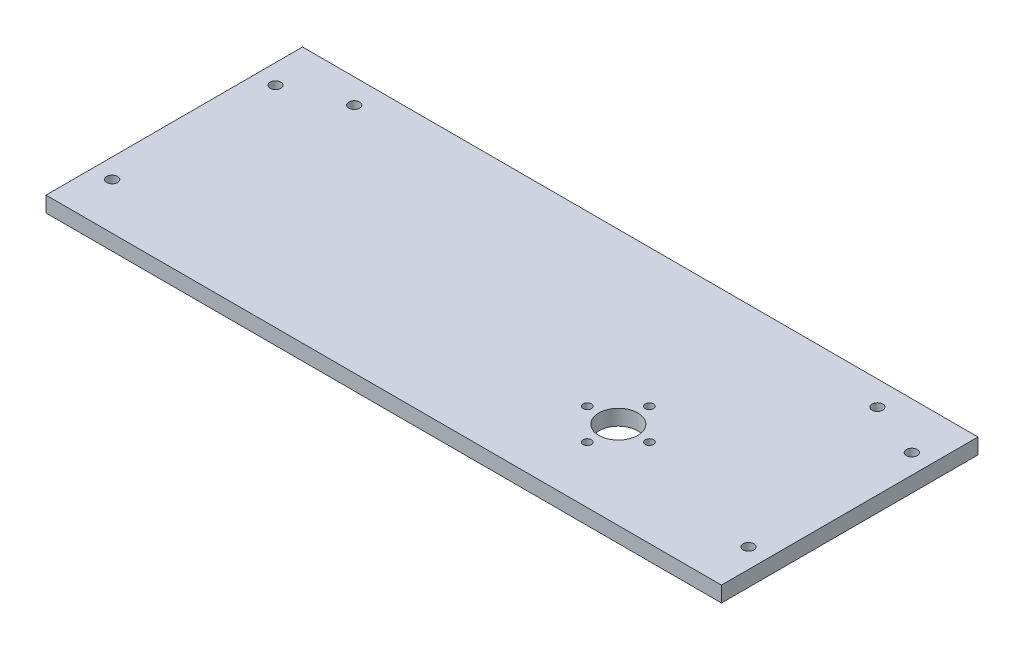
SolidWorks part; units mm, degrees
ref_plane "Front Plane" through (0, 0, 0) normal (0, 0, 1) x (1, 0, 0)
ref_plane "Top Plane" through (0, 0, 0) normal (0, 1, 0) x (1, 0, 0)
ref_plane "Right Plane" through (0, 0, 0) normal (1, 0, 0) x (0, 0, -1)
sketch "Sketch1" plane through (0, 0, 0) normal (0, 1, 0) x (1, 0, 0)
  line L1 (-138, 52.413) -> (138, 52.413)
  line L2 (-138, 52.413) -> (-138, -52.413)
  line L3 (-138, -52.413) -> (138, -52.413)
  line L4 (138, 52.413) -> (138, -52.413)
  line L5 (-138, 52.413) -> (138, -52.413) construction
  line L6 (-138, -52.413) -> (138, 52.413) construction
  point P0 (0, 0)
  dimension "D1" = 276
  dimension "D2" = 104.826
extrude "Boss-Extrude1" add sketch "Sketch1" along normal blind 6.35
sketch "Sketch2" plane through (0, 6.35, 0) normal (0, 1, 0) x (1, 0, 0)
  line L0 (138, 52.413) -> (-138, 52.413) construction
  line L1 (-138, -52.413) -> (138, -52.413) construction
  line L2 (0, -3.4925) -> (0, 3.4925) construction
  circle A0 centre (-130, 33.363) radius 2.2
  circle A1 centre (-130, -33.363) radius 2.2
  circle A2 centre (130, -33.363) radius 2.2
  circle A3 centre (130, 33.363) radius 2.2
  dimension "D1" = 4.4
  dimension "D2" = 19.05
  dimension "D3" = 19.05
  dimension "D4" = 260
extrude "Cut-Extrude1" cut sketch "Sketch2" against normal up to next
sketch "Sketch3" plane through (0, 6.35, 0) normal (0, 1, 0) x (1, 0, 0)
  line L0 (138, 52.413) -> (-138, 52.413) construction
  line L1 (-138, 52.413) -> (-138, -52.413) construction
  line L2 (138, -52.413) -> (138, 52.413) construction
  circle A0 centre (-106.885, 42.413) radius 2.2
  circle A1 centre (106.885, 42.413) radius 2.2
  dimension "D2" = 4.4
  dimension "D1" = 10
  dimension "D3" = 31.115
  dimension "D4" = 31.115
extrude "Cut-Extrude2" cut sketch "Sketch3" against normal up to next
sketch "Sketch4" plane through (0, 6.35, 0) normal (0, 1, 0) x (1, 0, 0)
  line L0 (138, -52.413) -> (138, 52.413) construction
  line L1 (-138, -52.413) -> (138, -52.413) construction
  circle A0 centre (60, -16.543) radius 7.9629
  dimension "D1" = 15.9258
  dimension "D2" = 78
  dimension "D3" = 35.87
extrude "Cut-Extrude3" cut sketch "Sketch4" against normal up to next
sketch "Sketch5" plane through (0, 6.35, 0) normal (0, 1, 0) x (1, 0, 0)
  line L0 (60, -16.543) -> (60, -3.843) construction
  circle A0 centre (60, -3.843) radius 1.7
  circle A2 centre (72.7, -16.543) radius 1.7
  circle A3 centre (60, -29.243) radius 1.7
  circle A4 centre (47.3, -16.543) radius 1.7
  point P13 (60, -16.543)
  dimension "D1" = 3.4
  dimension "D3" = 12.7
  dimension "D2" = 4
extrude "Cut-Extrude4" cut sketch "Sketch5" against normal up to next
equation "\"D4@Sketch3\"=\"D3@Sketch3\""
